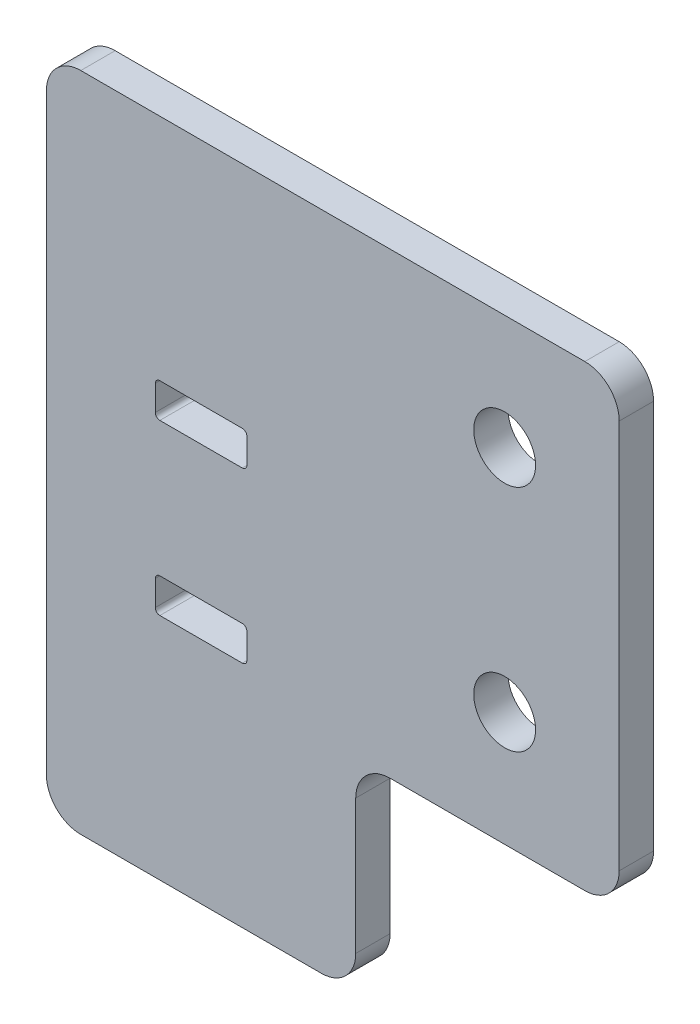
SolidWorks part; units mm, degrees
ref_plane "Ebene vorne" through (0, 0, 0) normal (0, 0, 1) x (1, 0, 0)
ref_plane "Ebene oben" through (0, 0, 0) normal (0, 1, 0) x (1, 0, 0)
ref_plane "Ebene rechts" through (0, 0, 0) normal (1, 0, 0) x (0, 0, -1)
sketch "Model" plane through (0, 0, 0) normal (0, 0, 1) x (1, 0, 0)
  line L0 (50, 20.75) -> (50, 54.75)
  line L1 (47, 57.75) -> (3, 57.75)
  line L2 (0, 54.75) -> (0, 3)
  line L3 (3, 0) -> (24, 0)
  line L4 (27, 3) -> (27, 14.75)
  line L5 (30, 17.75) -> (47, 17.75)
  line L6 (17.1, 34.75) -> (9.9, 34.75)
  line L7 (9.5, 35.15) -> (9.5, 37.35)
  line L8 (9.9, 37.75) -> (17.1, 37.75)
  line L9 (17.5, 37.35) -> (17.5, 35.15)
  line L10 (17.1, 20) -> (9.9, 20)
  line L11 (9.5, 20.4) -> (9.5, 22.6)
  line L12 (9.9, 23) -> (17.1, 23)
  line L13 (17.5, 22.6) -> (17.5, 20.4)
  circle A0 centre (40, 27.75) radius 2.7
  circle A1 centre (40, 47.75) radius 2.7
  arc A2 (50, 54.75) -> (47, 57.75) centre (47, 54.75) ccw
  arc A3 (3, 57.75) -> (0, 54.75) centre (3, 54.75) ccw
  arc A4 (0, 3) -> (3, 0) centre (3, 3) ccw
  arc A5 (24, 0) -> (27, 3) centre (24, 3) ccw
  arc A6 (30, 17.75) -> (27, 14.75) centre (30, 14.75) ccw
  arc A7 (47, 17.75) -> (50, 20.75) centre (47, 20.75) ccw
  arc A8 (9.5, 35.15) -> (9.9, 34.75) centre (9.9, 35.15) ccw
  arc A9 (9.9, 37.75) -> (9.5, 37.35) centre (9.9, 37.35) ccw
  arc A10 (17.5, 37.35) -> (17.1, 37.75) centre (17.1, 37.35) ccw
  arc A11 (17.1, 34.75) -> (17.5, 35.15) centre (17.1, 35.15) ccw
  arc A12 (9.5, 20.4) -> (9.9, 20) centre (9.9, 20.4) ccw
  arc A13 (9.9, 23) -> (9.5, 22.6) centre (9.9, 22.6) ccw
  arc A14 (17.5, 22.6) -> (17.1, 23) centre (17.1, 22.6) ccw
  arc A15 (17.1, 20) -> (17.5, 20.4) centre (17.1, 20.4) ccw
extrude "Aufsatz-Linear austragen1" add sketch "Model" along normal blind 3
